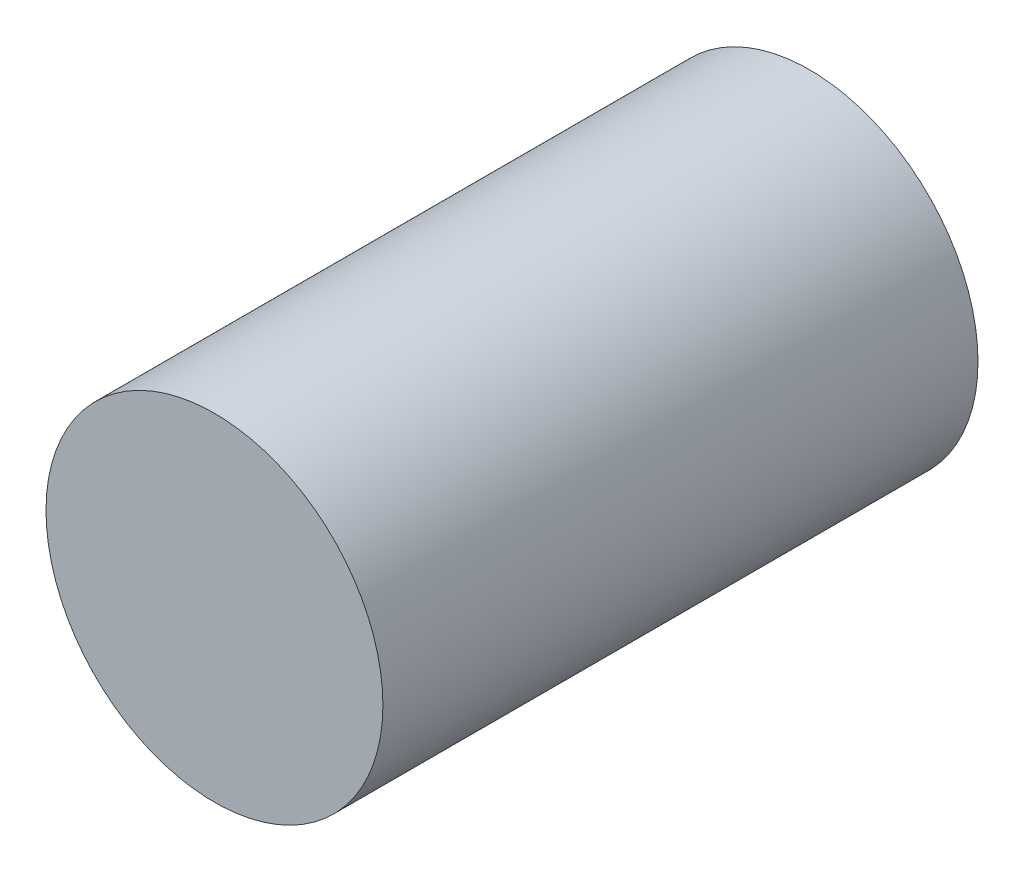
SolidWorks part; units mm, degrees
ref_plane "Ground" through (0, 0, 0) normal (0, 0, 1) x (1, 0, 0)
ref_plane "Right" through (0, 0, 0) normal (0, 1, 0) x (1, 0, 0)
ref_plane "Front" through (0, 0, 0) normal (1, 0, 0) x (0, 0, -1)
sketch "Sketch1" plane through (0, 0, 0) normal (0, 0, 1) x (1, 0, 0)
  circle A0 centre (0, 0) radius 13.5
  dimension "D1" = 27
extrude "Boss-Extrude1" add sketch "Sketch1" along normal blind 47.69 contours A0
